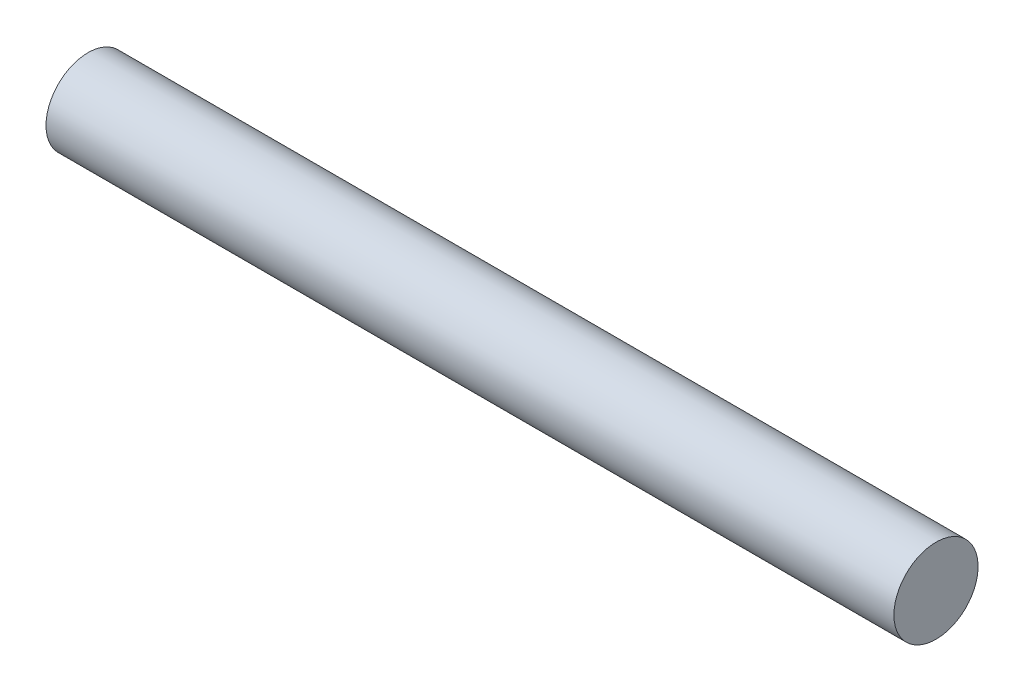
SolidWorks part; units mm, degrees
ref_plane "Piano frontale" through (0, 0, 0) normal (0, 0, 1) x (1, 0, 0)
ref_plane "Piano superiore" through (0, 0, 0) normal (0, 1, 0) x (1, 0, 0)
ref_plane "Piano destro" through (0, 0, 0) normal (1, 0, 0) x (0, 0, -1)
sketch "Schizzo1" plane through (0, 0, 0) normal (1, 0, 0) x (0, 0, -1)
  circle A0 centre (0, 0) radius 2.99
  dimension "D1" = 5.98
extrude "Estrusione-Estrusione1" add sketch "Schizzo1" along normal blind 60.26
